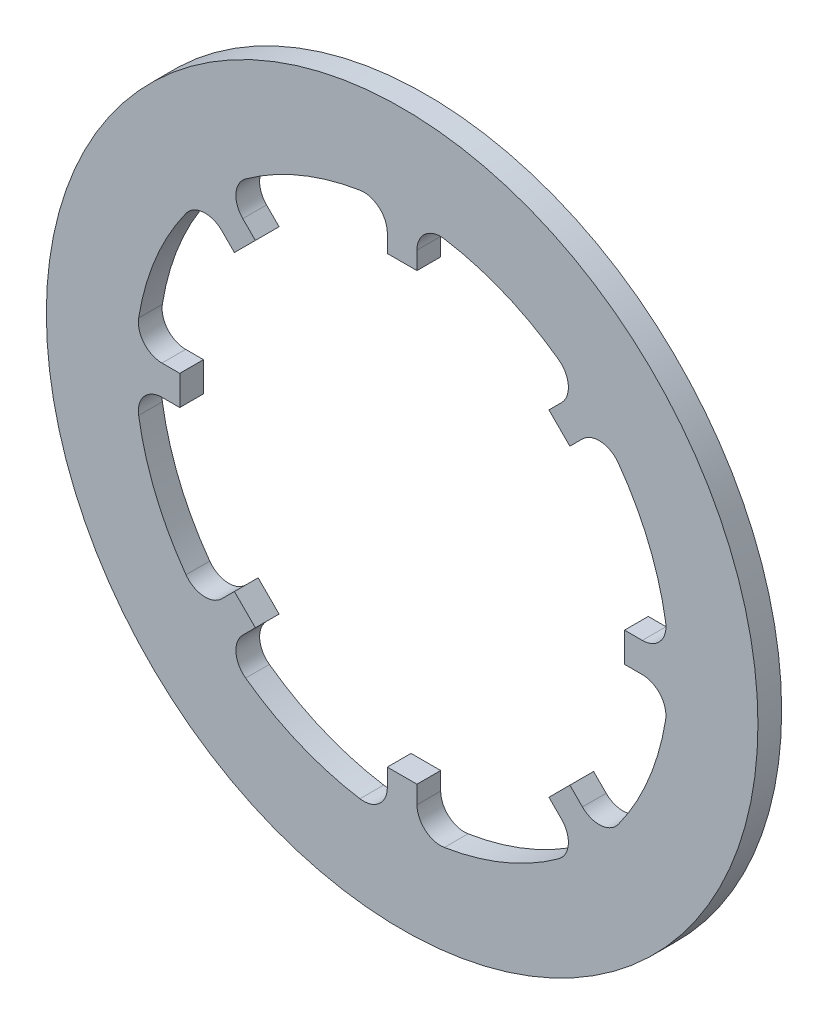
SolidWorks part; units mm, degrees
material "0.6010 (EN-GJL-100)"
ref_plane "Płaszczyzna przednia" through (0, 0, 0) normal (0, 0, 1) x (1, 0, 0)
ref_plane "Płaszczyzna górna" through (0, 0, 0) normal (0, 1, 0) x (1, 0, 0)
ref_plane "Płaszczyzna prawa" through (0, 0, 0) normal (1, 0, 0) x (0, 0, -1)
sketch "Szkic1" plane through (0, 0, 0) normal (0, 0, 1) x (1, 0, 0)
  circle A0 centre (0, 0) radius 120
  circle A1 centre (0, 0) radius 90
  dimension "D1" = 240
  dimension "D2" = 30
extrude "Dodanie-wyciągnięcie1" add sketch "Szkic1" along normal mid plane 8
sketch "Szkic2" plane through (0, 0, 0) normal (0, 0, 1) x (1, 0, 0)
  line L0 (5, 75) -> (-5, 75)
  line L1 (-5, 75) -> (-5, 81)
  line L2 (0, -4.4) -> (0, 4.4) construction
  line L3 (5, 75) -> (5, 81)
  arc A0 (-5, 81) -> (-14.2282, 88.8682) centre (-12.9684, 81) ccw
  circle A1 centre (0, 0) radius 90 construction
  arc A2 (14.2282, 88.8682) -> (-14.2282, 88.8682) centre (0, 0) ccw
  arc A3 (5, 81) -> (14.2282, 88.8682) centre (12.9684, 81) cw
  point P17 (0, 75)
  dimension "D4" = 180
  dimension "D2" = 6
  dimension "D3" = 75
  dimension "D1" = 5
extrude "Dodanie-wyciągnięcie2" add sketch "Szkic2" along normal up to surface (8 mm away) from surface at -4 up to face at (120, 0, 4) starting at face at (120, 0, -4)
pattern_circular "Szyk kołowy1" count 8 over 360 about axis through (0, 0, 0) along (0, 0, 1) of "Dodanie-wyciągnięcie2"
equation "\"D3@Szkic2\"=\"D4@Szkic2\"/2-15"
